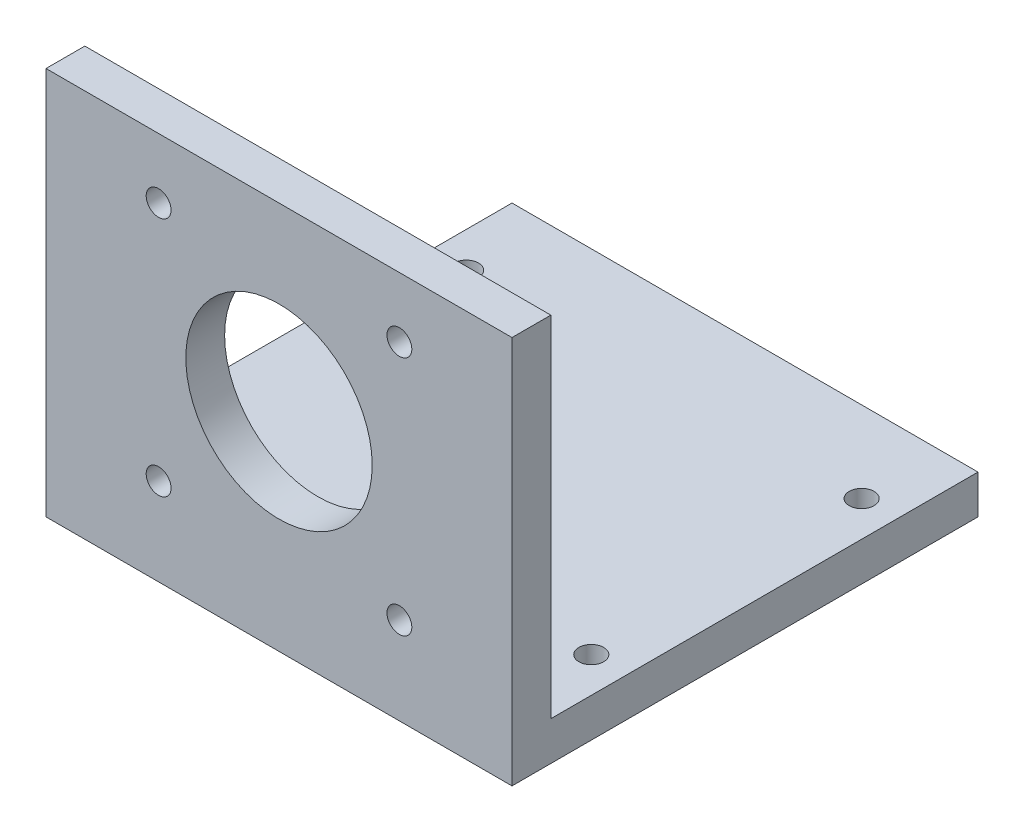
SolidWorks part; units mm, degrees
ref_plane "前视基准面" through (0, 0, 0) normal (0, 0, 1) x (1, 0, 0)
ref_plane "上视基准面" through (0, 0, 0) normal (0, 1, 0) x (1, 0, 0)
ref_plane "右视基准面" through (0, 0, 0) normal (1, 0, 0) x (0, 0, -1)
other "Configuration Table"
sketch "草图1" plane through (0, 0, 0) normal (1, 0, 0) x (0, 0, -1)
  line L0 (0, 0) -> (0, 50)
  line L1 (0, 50) -> (5, 50)
  line L2 (5, 50) -> (5, 5)
  line L3 (5, 5) -> (60, 5)
  line L4 (0, 0) -> (60, 0)
  line L5 (60, 0) -> (60, 5)
  dimension "D1" = 45
  dimension "D2" = 5
  dimension "D3" = 5
  dimension "D4" = 60
extrude "凸台-拉伸1" add sketch "草图1" along normal blind 60
sketch "草图4" plane through (0, 5, 0) normal (0, 1, 0) x (1, 0, 0)
  line L0 (60, 5) -> (60, 0) construction
  line L1 (0, 60) -> (60, 60)
  line L2 (0, 60) -> (0, 5)
  line L3 (0, 5) -> (60, 5)
  line L4 (60, 60) -> (60, 5)
  line L5 (60, 5) -> (0, 5) construction
hole_wizard "孔2" positions "草图6" profile "草图7" legacy end condition through all
sketch "草图6" plane through (0, 0, 0) normal (0, 0, 1) x (1, 0, 0)
  point P0 (30, 26.75)
sketch "草图7" plane through (30, 26.75, 0) normal (1, 0, 0) x (0, -1, 0)
  line L0 (0, 0) -> (0, 60)
  line L1 (0, 60) -> (12, 60)
  line L2 (12, 60) -> (12, 0)
  line L3 (12, 0) -> (0, 0)
  line L4 (0, 110) -> (0, -10) construction
  dimension "直径" = 24
  dimension "深度" = 60
hole_wizard "孔3" positions "草图10" profile "草图11" legacy end condition through all
sketch "草图10" plane through (0, 0, 0) normal (0, 0, 1) x (1, 0, 0)
  point P0 (14.5, 42.25)
  point P3 (45.5, 42.25)
  point P6 (45.5, 11.25)
  point P9 (14.5, 11.25)
sketch "草图11" plane through (14.5, 42.25, 0) normal (1, 0, 0) x (0, -1, 0)
  line L0 (0, 0) -> (0, 60)
  line L1 (0, 60) -> (1.6, 60)
  line L2 (1.6, 60) -> (1.6, 0)
  line L3 (1.6, 0) -> (0, 0)
  line L4 (0, 110) -> (0, -10) construction
  dimension "直径" = 3.2
  dimension "深度" = 60
hole_wizard "孔4" positions "草图12" profile "草图13" legacy end condition through all
sketch "草图12" plane through (0, 5, 0) normal (0, 1, 0) x (1, 0, 0)
  point P0 (55.4593, 14.749)
  point P2 (55.4593, 49.5575)
  point P13 (4.5407, 14.749)
  point P14 (4.5407, 49.5575)
sketch "草图13" plane through (55.4593, 5, -14.749) normal (1, 0, 0) x (0, 0, 1)
  line L0 (0, 0) -> (0, 5)
  line L1 (0, 5) -> (1.6, 5)
  line L2 (1.6, 5) -> (1.6, 0)
  line L3 (1.6, 0) -> (0, 0)
  line L4 (0, 110) -> (0, -10) construction
  dimension "直径" = 3.2
  dimension "深度" = 5
